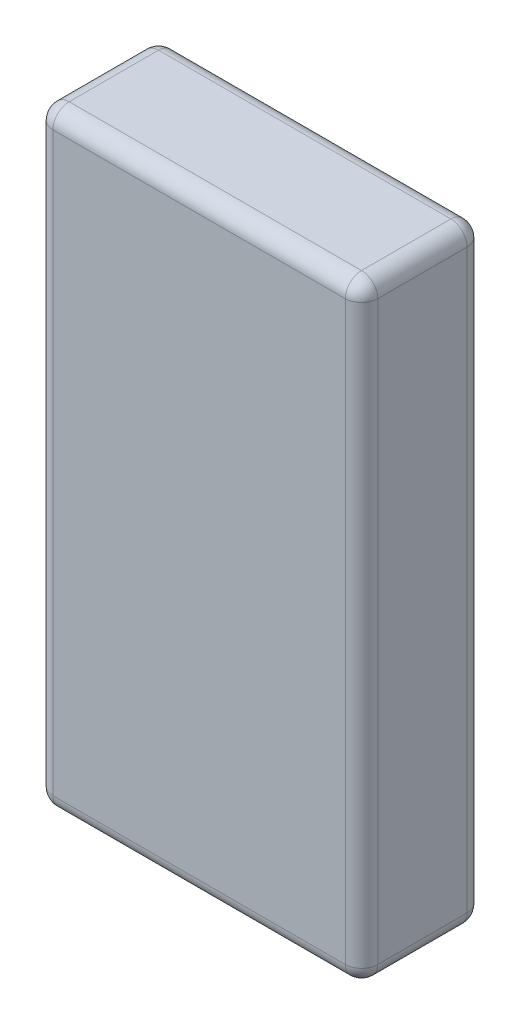
SolidWorks part; units mm, degrees
ref_plane "前视基准面" through (0, 0, 0) normal (0, 0, 1) x (1, 0, 0)
ref_plane "上视基准面" through (0, 0, 0) normal (0, 1, 0) x (1, 0, 0)
ref_plane "右视基准面" through (0, 0, 0) normal (1, 0, 0) x (0, 0, -1)
sketch "草图1" plane through (0, 0, 0) normal (0, 1, 0) x (1, 0, 0)
  line L1 (-20, 7.5) -> (20, 7.5)
  line L2 (-20, 7.5) -> (-20, -7.5)
  line L3 (-20, -7.5) -> (20, -7.5)
  line L4 (20, 7.5) -> (20, -7.5)
  line L5 (-20, 7.5) -> (20, -7.5) construction
  line L6 (-20, -7.5) -> (20, 7.5) construction
  point P0 (0, 0)
  dimension "D1" = 40
  dimension "D2" = 15
extrude "凸台-拉伸1" add sketch "草图1" along normal blind 75
fillet "圆角1" radius 2 12 edges at (20, 37.5, 7.5) (20, 75, 0) (0, 75, -7.5) (-20, 75, 0) (0, 75, 7.5) (0, 0, 7.5) (-20, 37.5, 7.5) (-20, 0, 0) (-20, 37.5, -7.5) (0, 0, -7.5) (20, 37.5, -7.5) (20, 0, 0)
